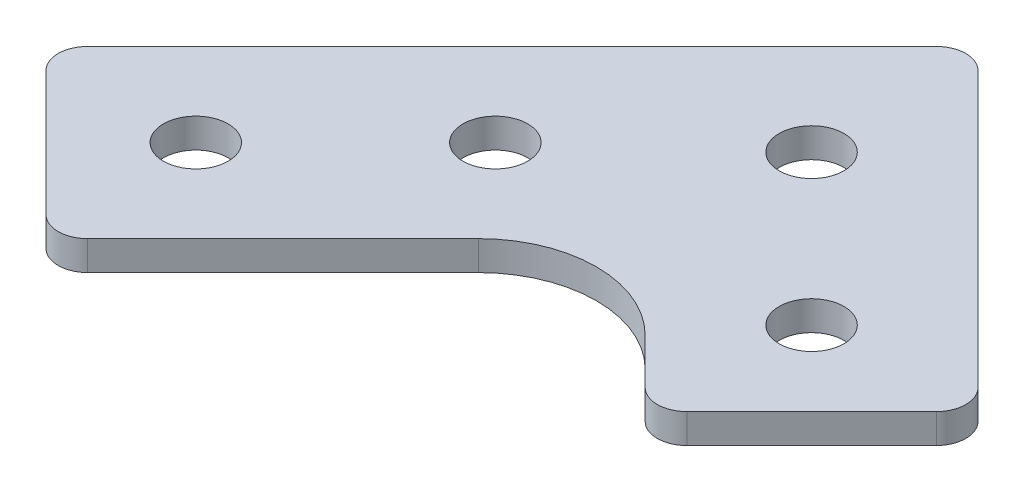
SolidWorks part; units mm, degrees
material "5052-H32"
ref_plane "Front Plane" through (0, 0, 0) normal (0, 0, 1) x (1, 0, 0)
ref_plane "Top Plane" through (0, 0, 0) normal (0, 1, 0) x (1, 0, 0)
ref_plane "Right Plane" through (0, 0, 0) normal (1, 0, 0) x (0, 0, -1)
sketch "Sketch1" plane through (0, 0, 0) normal (0, 1, 0) x (1, 0, 0)
  line L0 (-17.9605, 17.9605) -> (0, 35.921)
  line L5 (32.3289, -32.3289) -> (0, 0)
  line L6 (32.3289, -32.3289) -> (50.2894, -14.3684)
  line L7 (50.2894, -14.3684) -> (17.9605, 17.9605)
  line L9 (0, 0) -> (-32.3289, -32.3289)
  line L11 (-17.9605, 17.9605) -> (-50.2894, -14.3684)
  line L12 (-32.3289, -32.3289) -> (-50.2894, -14.3684)
  line L13 (0, 35.921) -> (17.9605, 17.9605)
  line L14 (-17.9605, 17.9605) -> (0, 0) construction
  line L15 (17.9605, 17.9605) -> (0, 0) construction
  line L16 (0, 0) -> (0, 35.921) construction
  dimension "D1" = 25.4
  dimension "D2" = 25.4
  dimension "D5" = 90
  dimension "D3" = 45.72
  dimension "D4" = 45.72
extrude "Boss-Extrude1" add sketch "Sketch1" along normal blind 3.175 contours L0 L13 L7 L6 L5 L9 L12 L11
sketch "Sketch2" plane through (0, 3.175, 0) normal (0, 1, 0) x (1, 0, 0)
  line L0 (-50.2894, -14.3684) -> (-32.3289, -32.3289) construction
  line L1 (-33.2269, -15.2664) -> (-41.3092, -23.3487) construction
  line L2 (50.2894, -14.3684) -> (32.3289, -32.3289) construction
  line L3 (33.2269, -15.2664) -> (41.3092, -23.3487) construction
  circle A0 centre (-33.2269, -15.2664) radius 3.4925
  circle A1 centre (33.2269, -15.2664) radius 3.4925
  dimension "D1" = 6.985
  dimension "D2" = 11.43
sketch "Sketch7" plane through (0, 3.175, 0) normal (0, 1, 0) x (1, 0, 0)
  line L0 (-50.2894, -14.3684) -> (-32.3289, -32.3289) construction
  line L1 (-33.2269, -15.2664) -> (-41.3092, -23.3487) construction
  line L2 (50.2894, -14.3684) -> (32.3289, -32.3289) construction
  line L3 (33.2269, -15.2664) -> (41.3092, -23.3487) construction
  circle A0 centre (-33.2269, -15.2664) radius 3.4925
  circle A1 centre (33.2269, -15.2664) radius 3.4925
  dimension "D1" = 6.985
  dimension "D2" = 11.43
extrude "Cut-Extrude2" cut sketch "Sketch2" against normal blind 3.175 contours A0
pattern_linear "LPattern5" count 2 spacing 22.86 along (0.7071, 0, -0.7071) of "Cut-Extrude2"
extrude "Cut-Extrude3" cut sketch "Sketch7" against normal blind 3.175 contours A1
pattern_linear "LPattern6" count 3 spacing 22.86 along (-0.7071, 0, -0.7071) of "Cut-Extrude3"
sketch "Sketch8" plane through (0, 3.175, 0) normal (0, 1, 0) x (1, 0, 0)
  line L6 (32.3289, -32.3289) -> (50.2894, -14.3684) construction
  line L7 (32.3289, -32.3289) -> (50.2894, -14.3684)
  line L8 (32.3289, -32.3289) -> (50.2894, -14.3684)
  line L9 (32.3289, -32.3289) -> (16.1645, -16.1645)
  line L10 (50.2894, -14.3684) -> (34.125, 1.7961)
  line L11 (16.1645, -16.1645) -> (34.125, 1.7961)
  circle M4 centre (33.2269, -15.2664) radius 3.4925
  line M10 (0, 0) -> (32.3289, -32.3289)
  line M11 (32.3289, -32.3289) -> (50.2894, -14.3684)
  line M12 (50.2894, -14.3684) -> (0, 35.921)
  dimension "D2" = 22.86
extrude "Cut-Extrude4" cut sketch "Sketch8" against normal through all contours L11 M10 M11 M12 M4
fillet "Fillet1" radius 12.7 1 edges at (0, 1.5875, 0)
fillet "Fillet2" radius 3.175 5 edges at (0, 1.5875, -35.921) (34.125, 1.5875, -1.7961) (16.1645, 1.5875, 16.1645) (-50.2894, 1.5875, 14.3684) (-32.3289, 1.5875, 32.3289)
equation "\"InnerAngle\"= 90"
equation "\"StockThickness\"= .125in"
equation "\"HoleDiameter\"= .275in"
equation "\"BarWidth\"= 1in"
equation "\"HoleSpacing\"=0.9"
equation "\"AdditionalHoleCount\"= 1"
equation "\"D1@Sketch1\"=\"BarWidth\""
equation "\"D2@Sketch1\"= \"BarWidth\""
equation "\"WingLength\"= ( \"AdditionalHoleCount\" + 1 ) * \"HoleSpacing\""
equation "\"D5@Sketch1\"=\"InnerAngle\""
equation "\"D1@Boss-Extrude1\"=\"StockThickness\""
equation "\"D1@Sketch2\"=\"HoleDiameter\""
equation "\"D2@Sketch2\"=\"HoleSpacing\"/2"
equation "\"D3@LPattern5\"=\"HoleSpacing\""
equation "\"D1@LPattern5\"=\"AdditionalHoleCount\"+1"
equation "\"D2@Sketch7\"=\"HoleSpacing\"/2"
equation "\"D1@Sketch7\"=\"HoleDiameter\""
equation "\"D3@LPattern6\"=\"HoleSpacing\""
equation "\"D1@LPattern6\"=\"AdditionalHoleCount\"+2"
equation "\"D3@Sketch1\"=\"WingLength\""
equation "\"D4@Sketch1\"=\"WingLength\""
equation "\"D2@Sketch8\"=\"HoleSpacing\""
